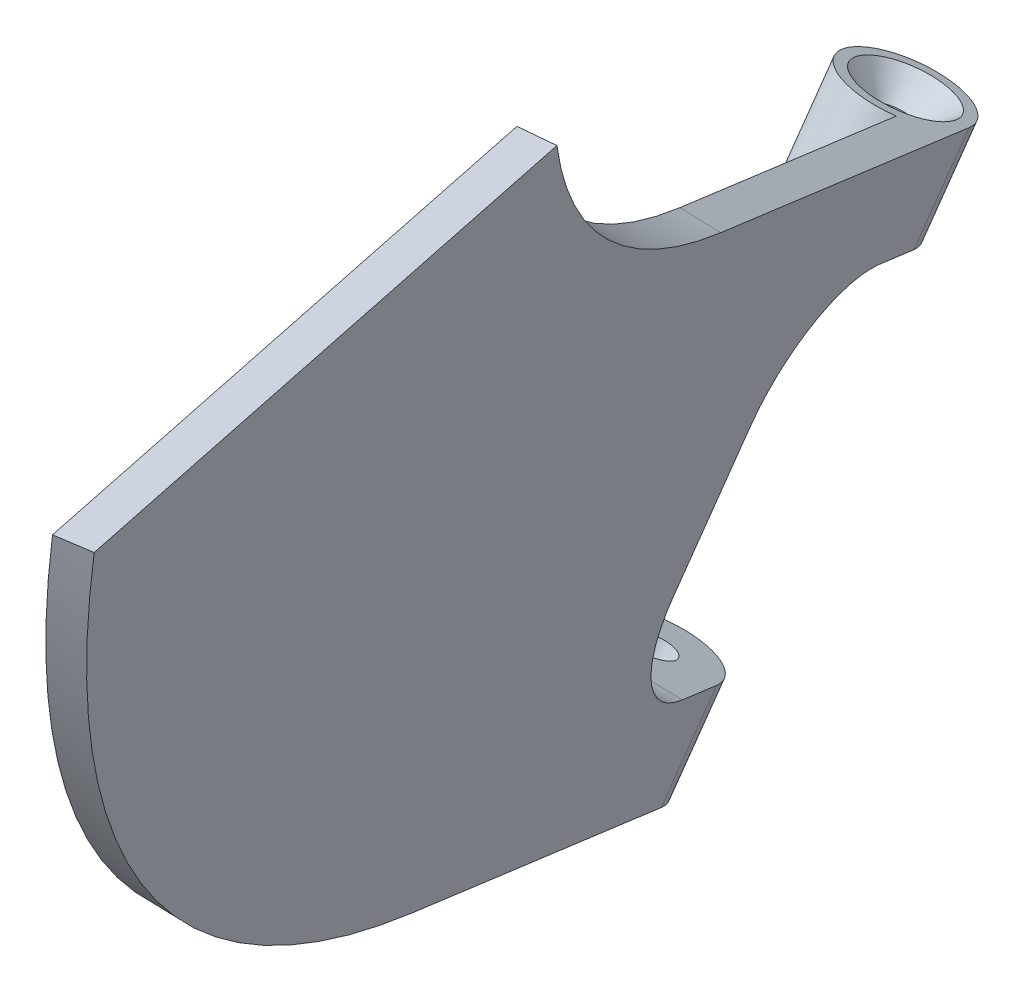
SolidWorks part; units mm, degrees
ref_plane "Front Plane" through (0, 0, 0) normal (0, 0, 1) x (1, 0, 0)
ref_plane "Top Plane" through (0, 0, 0) normal (0, 1, 0) x (1, 0, 0)
ref_plane "Right Plane" through (0, 0, 0) normal (1, 0, 0) x (0, 0, -1)
sketch "Sketch2" plane through (0, 0, 0) normal (0, 1, 0) x (1, 0, 0)
  line L0 (151.3, 0) -> (-151.3, 0) construction
  dimension "D1" = 302.6
ref_plane "Plane1" through (0, 0, 0) normal (0, 0.4067, 0.9135) x (-1, 0, 0)
sketch "Sketch3" plane through (0, 0, 0) normal (0, 0.4067, 0.9135) x (-1, 0, 0)
  line L0 (-136.8, 32.05) -> (-134.1, 32.05) construction
  line L1 (151.3, 176.2) -> (-151.3, 176.2) construction
  line L2 (151.3, 176.2) -> (151.3, 0) construction
  line L3 (151.3, 0) -> (-151.3, 0) construction
  line L4 (-151.3, 176.2) -> (-151.3, 0) construction
  line L5 (-151.3, 0) -> (151.3, 0) construction
  line L6 (-137.2598, 44.7696) -> (-140.8783, 19.0226) construction
  line L7 (-147.6, 46.65) -> (-134.1, 46.65) construction
  line L8 (-147.6, 46.65) -> (-147.6, 17.45) construction
  line L9 (-147.6, 17.45) -> (-134.1, 17.45) construction
  line L10 (-134.1, 46.65) -> (-134.1, 17.45) construction
  line L11 (-137.2598, 44.7696) -> (-142.6073, 45.5211) construction
  line L12 (-140.8783, 19.0226) -> (-146.2258, 19.7741) construction
  line L13 (-142.6073, 45.5211) -> (-146.2258, 19.7741) construction
  line L14 (-140.8783, 19.0226) -> (-133.9165, 18.0442) construction
  line L15 (-133.9165, 18.0442) -> (-134, 17.45) construction
  line L16 (-142.4371, 45.2952) -> (-137.4857, 44.5993)
  line L17 (-142.4371, 45.2952) -> (-145.9999, 19.9443)
  line L18 (-137.4857, 44.5993) -> (-141.0486, 19.2485)
  line L19 (-145.9999, 19.9443) -> (-141.0486, 19.2485)
  point P12 (-136.8, 32.05)
  dimension "D1" = 176.2
  dimension "D2" = 302.6
  dimension "D3" = 144.15
  dimension "D4" = 14.5
  dimension "D5" = 29.2
  dimension "D6" = 3.7
  dimension "D7" = 17.2
  dimension "D8" = 26
  dimension "D9" = 8
  dimension "D10" = 5.4
  dimension "D11" = 0.6
  dimension "D12" = 0.1
  dimension "D13" = 1.3742
  dimension "D14" = 5
  dimension "D15" = 0.2
  dimension "D16" = 0.2
  dimension "D17" = 0.2
extrude "Boss-Extrude1" add sketch "Sketch3" against normal blind 5
sketch "Sketch4" plane through (-3.4836, -22.6444, 10.0819) normal (-0.1392, -0.9047, 0.4028) x (0.9903, -0.1271, 0.0566)
  line L0 (152.7707, 16.0361) -> (147.2579, -3.1891) construction
  line L1 (142.3548, -5) -> (147.3548, 0) construction
  line L2 (152.7707, 16.0361) -> (151.2326, 16.4772) construction
  line L3 (151.2326, 16.4772) -> (146.3628, -0.506) construction
  line L4 (147.3548, -5) -> (147.3548, 0) construction
  line L5 (147.3548, -2.8514) -> (147.3548, -5)
  line L6 (147.3548, -5) -> (144.8548, -5)
  line L7 (142.3548, -5) -> (147.3548, -5) construction
  line L8 (147.2579, -3.1891) -> (147.3548, -2.8514)
  line L12 (142.3548, -2.5) -> (142.3548, -5)
  line L13 (142.3548, -5) -> (144.8548, -5)
  line L14 (142.3548, 0) -> (142.3548, -2.5)
  line L15 (142.3548, 0) -> (144.8548, 0)
  line L16 (144.8548, 0) -> (146.5079, 0)
  line L17 (146.5079, 0) -> (146.3628, -0.506)
  line L18 (142.3548, 0) -> (147.3548, 0) construction
  arc A0 (147.2579, -3.1891) -> (146.3628, -0.506) centre (144.8548, -2.5) cw construction
  arc A1 (144.8548, -5) -> (147.2579, -3.1891) centre (144.8548, -2.5) ccw
  arc A3 (142.3548, -2.5) -> (144.8548, -5) centre (144.8548, -2.5) ccw
  arc A4 (142.3548, -2.5) -> (144.8548, 0) centre (144.8548, -2.5) cw
  arc A5 (144.8548, 0) -> (146.3628, -0.506) centre (144.8548, -2.5) cw
  dimension "D2" = 2.5
  dimension "D1" = 1.6
  dimension "D3" = 16
  dimension "D4" = 20
extrude "Cut-Extrude1" cut sketch "Sketch4" against normal through all contours A1 L6 L8 | A3 L5 L6 | L5 A4 L8 | L8 A5 L17
ref_plane "Plane2" through (135.5824, -33.3758, -28.1152) normal (0.9519, -0.2343, -0.1974) x (-0.191, 0.0501, -0.9803)
sketch3d "3DSketch1"
  line L0 (149.6285, 0, 0) -> (156.8218, 0, 34.6885) construction
  line L1 (156.8218, 0, 34.6885) -> (151.3, -80.4834, 35.8335) construction
  line L2 (151.3, -160.9667, 71.667) -> (151.3, 0, 0) construction
  line L3 (151.3, 0, 0) -> (-151.3, 0, 0) construction
  line L4 (145.904, -19.5049, 5.1932) -> (150.827, -13.0853, 21.3129)
  line L5 (145.904, -19.5049, 5.1932) -> (142.3412, -42.664, 15.5044)
  line L6 (142.3412, -42.664, 15.5044) -> (147.2641, -36.2444, 31.624)
  line L7 (156.8218, 0, 34.6885) -> (162.2766, 0, 60.9937)
  line L8 (156.8218, 0, 34.6885) -> (160.157, 10.0034, 38.8972) construction
  line L9 (162.2766, 0, 60.9937) -> (160.157, 10.0034, 38.8972) construction
  line L10 (142.3412, -42.664, 15.5044) -> (139.9614, -42.0782, 15.9978) construction
  arc A0 (150.827, -13.0853, 21.3129) -> (156.8218, 0, 34.6885) centre (154.5149, 10.8871, 10.6397) ccw
  arc A1 (147.2641, -36.2444, 31.624) -> (162.2766, 0, 60.9937) centre (154.5149, 10.8871, 10.6397) ccw
  arc A2 (142.3412, -42.664, 15.5044) -> (141.4547, -41.4589, 17.9048) centre (139.9614, -42.0782, 15.9978) ccw construction
  point P5 (104.9215, 23.0954, 20.9237)
  point P10 (129.2903, 17.0966, 15.8704)
  point P20 (140.3093, -39.8166, 14.9909)
  dimension "D1" = 115
extrude "Boss-Extrude2" add sketch "3DSketch1" along direction (-0.9519, 0.2343, 0.1974) on the side of the normal blind 1.6 contours L7 A1 L6 L5 L4 A0
other "SurfaceCut1"
sketch "Sketch7" plane through (135.5824, -33.3758, -28.1152) normal (0.9519, -0.2343, -0.1974) x (-0.191, 0.0501, -0.9803)
  line L0 (-42.6605, 14.9503) -> (-33.5558, 10.8146)
  line L1 (-42.6605, 14.9503) -> (-49.443, 0.0185)
  line L2 (-33.5558, 10.8146) -> (-40.3382, -4.1171)
  line L3 (-49.443, 0.0185) -> (-40.3382, -4.1171)
  line L4 (-42.2406, -8.3053) -> (-31.6534, 15.0028) construction
  line L5 (-50.3507, 23.4957) -> (-33.9295, 16.0367) construction
  line L6 (-44.5168, -7.2714) -> (-60.9379, 0.1875) construction
  dimension "D1" = 4.6
  dimension "D2" = 4.6
  dimension "D3" = 10
extrude "Cut-Extrude2" cut sketch "Sketch7" against normal up to next
fillet "Fillet1" radius 5 2 edges at (146.5494, -20.8093, 13.9071) (144.267, -35.6456, 20.5127)
sketch "Sketch8" plane through (-3.4836, -22.6444, 10.0819) normal (-0.1392, -0.9047, 0.4028) x (-0.9903, 0.1271, -0.0566)
  circle A0 centre (-144.8548, 2.5) radius 0.9
  arc A1 (-146.3628, 0.506) -> (-147.2579, 3.1891) centre (-144.8548, 2.5) ccw construction
  dimension "D1" = 1.8
extrude "Cut-Extrude3" cut sketch "Sketch8" against normal through all
chamfer "Chamfer1" distance 1.1 angle 45 2 edges at (143.5242, -18.553, 6.5089) (139.9614, -42.4443, 15.1756)
equation "\"LCD_Height\"= 158mm"
equation "\"LCD_Width\"= 268mm"
equation "\"LCD_PCB_Height\"= 10mm"
equation "\"LCD_PCB_Width\"= 189"
equation "\"LCD_PCB_LOff\"= 38.5"
equation "\"LCD_Thick\"= 2.9mm"
equation "\"LCD_TBezel\"= 4.6mm"
equation "\"LCD_LBezel\"= 4.94mm"
equation "\"LCD_RBezel\"= 6.94mm"
equation "\"LCD_BBezel\"= 9.4mm"
equation "\"Wing_Height\"= 11.5mm"
equation "\"Wing_Width\"= 5mm"
equation "\"Wing_Corner\"= 1mm"
equation "\"Wing_Hole_VOff\"= 3.5mm"
equation "\"Wing_Hole_HOff\"= 2.8mm"
equation "\"Wing_Spacing\"= 128.9 + 2 * \"Wing_Hole_VOff\" - \"Wing_Height\""
equation "\"Wing_TOff\"= 8.35 - \"Wing_Hole_VOff\""
equation "\"Wing_DOff\"= 0.7mm"
equation "\"Wing_Thick\"= 0.3mm"
equation "\"Print_Gap\"= 0.2mm"
equation "\"Pin1_Pos\"= 89.75mm"
equation "\"Pin_Space\"= 0.5mm"
equation "\"Pin_num\"= 30"
equation "\"Min_Thick\"= 1.2mm"
equation "\"Nut_Width\"= 4.8mm"
equation "\"Nut_Height\"= 5.6mm"
equation "\"Nut_Thick\"= 1.6mm"
equation "\"Screw_Hole\"= 2.2mm"
equation "\"Screw_Chamf\"= 0.9mm"
equation "\"Bezel_Gap\"= 0.4mm"
equation "\"USB_Width\"= 16mm"
equation "\"Corner_Radius\"= 6mm"
equation "\"Stand_Tilt\"= 8"
equation "\"Screen_Tilt\"= 24"
equation "\"Stand_Splay\"= 16"
equation "\"D1@Sketch2\"=\"LCD_Width\" + \"Print_Gap\" + 2 * \"USB_Width\" + 2 * \"Min_Thick\""
equation "\"D1@Sketch3\"=\"Min_Thick\" + \"Print_Gap\" + \"LCD_Height\" + \"LCD_PCB_Height\" + \"Nut_Height\" + \"Min_Thick\""
equation "\"D2@Sketch3\"=\"LCD_Width\" + 2 * \"Min_Thick\" + 2 * \"USB_Width\" + \"Print_Gap\""
equation "\"D3@Sketch3\"=\"Min_Thick\" + \"Print_Gap\" / 2 + \"Nut_Height\" + \"Wing_TOff\" + \"Wing_Height\" - \"Wing_Hole_VOff\" + \"Wing_Spacing\""
equation "\"D4@Sketch3\"=\"Min_Thick\" + \"USB_Width\" + \"Print_Gap\" / 2 - \"Wing_Hole_HOff\""
equation "\"D5@Sketch3\"=\"Nut_Width\" + 2 * \"Min_Thick\" + 22"
equation "\"D6@Sketch3\"= 3 * \"Min_Thick\" + \"Print_Gap\" / 2"
equation "\"D9@Sketch3\"=\"Stand_Tilt\""
equation "\"D11@Sketch3\"=\"Min_Thick\" / 2"
equation "\"D12@Sketch3\"= \"Print_Gap\" / 2"
equation "\"D13@Sketch3\"=2.7 * tan(\"Stand_Splay\") + \"Min_Thick\" / 2"
equation "\"D15@Sketch3\"= \"Print_Gap\""
equation "\"D16@Sketch3\"= \"Print_Gap\""
equation "\"D17@Sketch3\"=\"Print_Gap\""
equation "\"D1@Sketch8\"=\"Screw_Hole\" - 2 *\"Print_Gap\" "
equation "\"D1@Chamfer1\"=\"Screw_Chamf\" + \"Print_Gap\""
equation "\"D3@Sketch4\"= \"Stand_Splay\""
